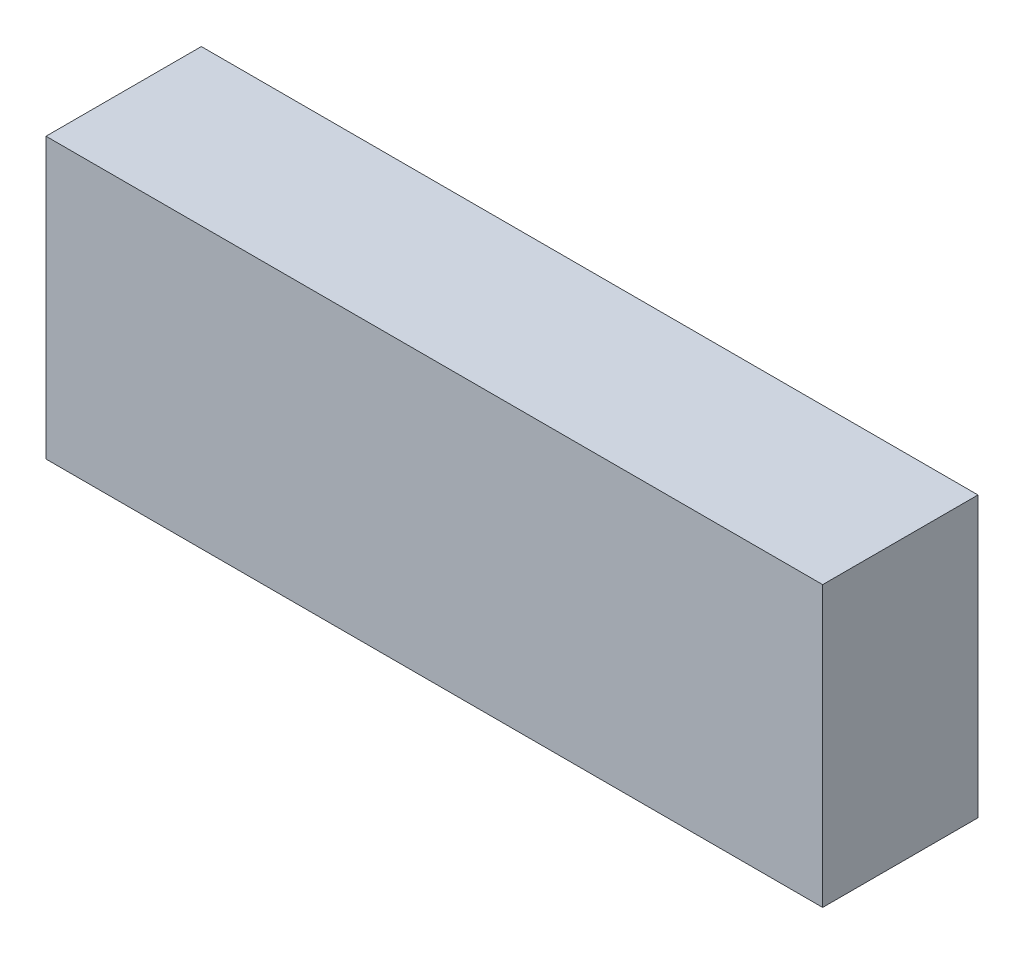
SolidWorks part; units mm, degrees
ref_plane "Front Plane" through (0, 0, 0) normal (0, 0, 1) x (1, 0, 0)
ref_plane "Top Plane" through (0, 0, 0) normal (0, 1, 0) x (1, 0, 0)
ref_plane "Right Plane" through (0, 0, 0) normal (1, 0, 0) x (0, 0, -1)
sketch "Sketch1" plane through (0, 0, 0) normal (0, 0, 1) x (1, 0, 0)
  line L1 (0, 0) -> (50, 0)
  line L2 (0, 0) -> (0, 18)
  line L3 (0, 18) -> (50, 18)
  line L4 (50, 0) -> (50, 18)
  dimension "D1" = 18
  dimension "D2" = 50
extrude "Boss-Extrude1" add sketch "Sketch1" along normal blind 10
